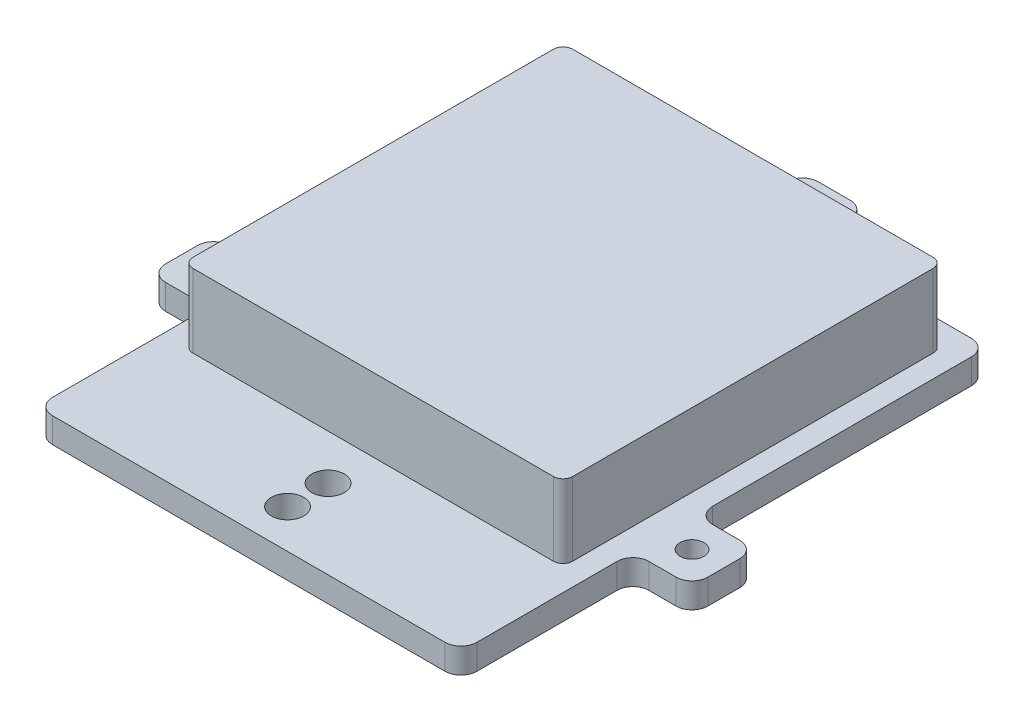
SolidWorks part; units mm, degrees
ref_plane "Front Plane" through (0, 0, 0) normal (0, 0, 1) x (1, 0, 0)
ref_plane "Top Plane" through (0, 0, 0) normal (0, 1, 0) x (1, 0, 0)
ref_plane "Right Plane" through (0, 0, 0) normal (1, 0, 0) x (0, 0, -1)
sketch "Sketch1" plane through (0, 0, 0) normal (0, 1, 0) x (1, 0, 0)
  line L0 (-1, 8.25) -> (-1, 10.1)
  line L1 (6.65, 8.25) -> (1, 8.25)
  line L2 (6.65, 8.25) -> (6.65, -0.8585)
  line L3 (6.65, -8.25) -> (-6.65, -8.25)
  line L4 (-6.65, 8.25) -> (-6.65, -0.8585)
  line L5 (6.65, 8.25) -> (-6.65, -8.25) construction
  line L6 (6.65, -8.25) -> (-6.65, 8.25) construction
  line L7 (-1, 10.1) -> (1, 10.1)
  line L8 (1, 10.1) -> (1, 8.25)
  line L9 (6.65, -2.8585) -> (8.5, -2.8585)
  line L10 (8.5, -2.8585) -> (8.5, -0.8585)
  line L11 (8.5, -0.8585) -> (6.65, -0.8585)
  line L12 (-6.65, -2.8585) -> (-8.5, -2.8585)
  line L13 (-8.5, -2.8585) -> (-8.5, -0.8585)
  line L14 (-8.5, -0.8585) -> (-6.65, -0.8585)
  line L15 (-6.65, -2.8585) -> (-6.65, -8.25)
  line L16 (6.65, -2.8585) -> (6.65, -8.25)
  line L17 (-1, 8.25) -> (-6.65, 8.25)
  circle A0 centre (-7.5, -1.8585) radius 0.375
  circle A1 centre (7.5, -1.8585) radius 0.375
  circle A2 centre (0, 9.1415) radius 0.375
  point P0 (0, 0)
  dimension "D3" = 0.75
  dimension "D1" = 16.5
  dimension "D2" = 13.3
  dimension "D4" = 7.5
  dimension "D5" = 7.5
  dimension "D6" = 9.1415
  dimension "D7" = 8.5
  dimension "D8" = 8.5
  dimension "D9" = 2
  dimension "D10" = 2
  dimension "D11" = 2
  dimension "D12" = 1.85
  dimension "D13" = 5.65
  dimension "D14" = 1
  dimension "D15" = 11
  dimension "D16" = 10
  dimension "D17" = 11
extrude "Boss-Extrude1" add sketch "Sketch1" along normal blind 0.7874
sketch "Sketch2" plane through (0, 0.7874, 0) normal (0, 1, 0) x (1, 0, 0)
  line L0 (6.65, 8.25) -> (1, 8.25) construction
  line L1 (5.65, 7.55) -> (-5.65, 7.55)
  line L2 (5.95, 7.25) -> (5.95, -4.05)
  line L3 (5.65, -4.35) -> (-5.65, -4.35)
  line L4 (-5.95, 7.25) -> (-5.95, -4.05)
  line L5 (5.95, 7.55) -> (-5.95, -4.35) construction
  line L6 (5.95, -4.35) -> (-5.95, 7.55) construction
  line L7 (0, 0) -> (0, 1.6) construction
  arc A0 (-5.65, 7.55) -> (-5.95, 7.25) centre (-5.65, 7.25) ccw
  arc A1 (-5.65, -4.35) -> (-5.95, -4.05) centre (-5.65, -4.05) cw
  arc A2 (5.95, -4.05) -> (5.65, -4.35) centre (5.65, -4.05) cw
  arc A3 (5.65, 7.55) -> (5.95, 7.25) centre (5.65, 7.25) cw
  point P0 (0, 0)
  dimension "D4" = 0.3
  dimension "D1" = 11.9
  dimension "D2" = 11.9
  dimension "D3" = 0.7
extrude "Boss-Extrude2" add sketch "Sketch2" along normal blind 2.3
fillet "Fillet1" radius 0.5 16 edges at (-1, 0.3937, -8.25) (-6.65, 0.3937, -8.25) (-6.65, 0.3937, 0.8585) (-8.5, 0.3937, 0.8585) (-8.5, 0.3937, 2.8585) (-6.65, 0.3937, 2.8585) (-6.65, 0.3937, 8.25) (6.65, 0.3937, 2.8585) (6.65, 0.3937, 8.25) (8.5, 0.3937, 2.8585) (8.5, 0.3937, 0.8585) (6.65, 0.3937, 0.8585) (1, 0.3937, -8.25) (6.65, 0.3937, -8.25) (-1, 0.3937, -10.1) (1, 0.3937, -10.1)
sketch "Sketch3" plane through (0, 0.7874, 0) normal (0, 1, 0) x (1, 0, 0)
  line L0 (0, -8.25) -> (0, 11.0218) construction
  circle A0 centre (0, -5.7662) radius 0.508
  circle A1 centre (0, -7.0362) radius 0.508
  point P7 (0, -7.0362)
  dimension "D1" = 1.27
  dimension "D2" = 1.016
extrude "Cut-Extrude1" cut sketch "Sketch3" against normal up to surface (0.7874 mm away) up to face at (7.5, 0, 2.2335)
